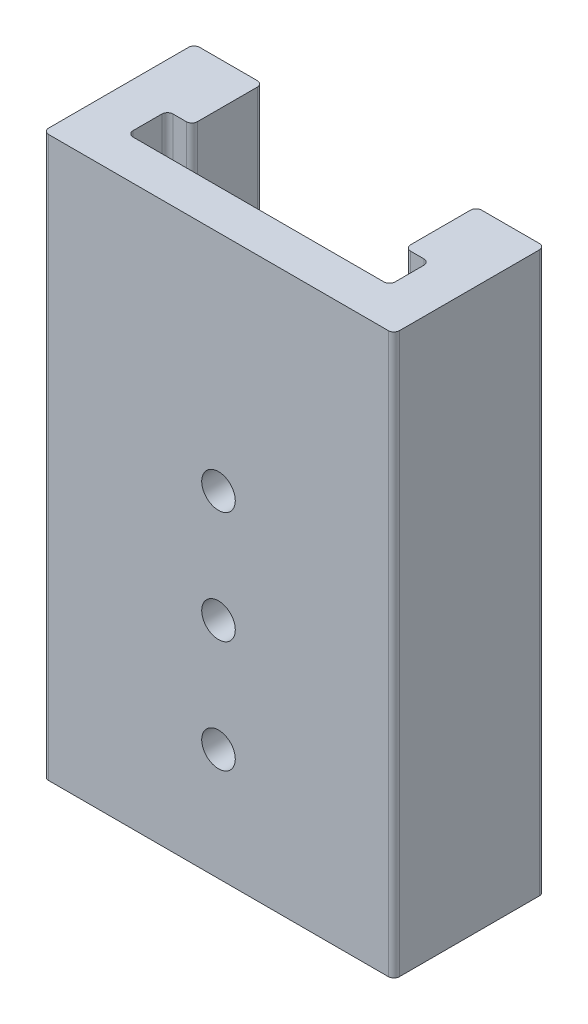
SolidWorks part; units mm, degrees
ref_plane "Front Plane" through (0, 0, 0) normal (0, 0, 1) x (1, 0, 0)
ref_plane "Top Plane" through (0, 0, 0) normal (0, 1, 0) x (1, 0, 0)
ref_plane "Right Plane" through (0, 0, 0) normal (1, 0, 0) x (0, 0, -1)
sketch "Sketch1" plane through (0, 0, 0) normal (0, 1, 0) x (1, 0, 0)
  line L0 (-15.1766, 0) -> (15.1766, 0)
  line L1 (15.6766, 0.5) -> (15.6766, 12.9937)
  line L2 (15.1766, 13.4938) -> (10.025, 13.4938)
  line L3 (9.525, 12.9937) -> (9.525, 7.6438)
  line L4 (10.025, 7.1437) -> (11.2078, 7.1437)
  line L5 (11.7078, 6.6437) -> (11.7078, 4.0719)
  line L6 (11.2078, 3.5719) -> (-11.2078, 3.5719)
  line L7 (0, 3.5719) -> (0, 0) construction
  line L8 (-11.7078, 6.6437) -> (-11.7078, 4.0719)
  line L9 (-10.025, 7.1437) -> (-11.2078, 7.1437)
  line L10 (-9.525, 12.9937) -> (-9.525, 7.6438)
  line L11 (-15.1766, 13.4937) -> (-10.025, 13.4938)
  line L12 (-15.6766, 0.5) -> (-15.6766, 12.9937)
  arc A0 (-15.6766, 0.5) -> (-15.1766, 0) centre (-15.1766, 0.5) ccw
  arc A1 (15.1766, 0) -> (15.6766, 0.5) centre (15.1766, 0.5) ccw
  arc A2 (15.6766, 12.9937) -> (15.1766, 13.4938) centre (15.1766, 12.9938) ccw
  arc A3 (10.025, 13.4938) -> (9.525, 12.9937) centre (10.025, 12.9938) ccw
  arc A4 (9.525, 7.6438) -> (10.025, 7.1437) centre (10.025, 7.6437) ccw
  arc A5 (11.2078, 7.1437) -> (11.7078, 6.6437) centre (11.2078, 6.6437) cw
  arc A6 (11.7078, 4.0719) -> (11.2078, 3.5719) centre (11.2078, 4.0719) cw
  arc A7 (-11.7078, 4.0719) -> (-11.2078, 3.5719) centre (-11.2078, 4.0719) ccw
  arc A8 (-11.7078, 6.6437) -> (-11.2078, 7.1437) centre (-11.2078, 6.6437) cw
  arc A9 (-10.025, 7.1437) -> (-9.525, 7.6438) centre (-10.025, 7.6437) ccw
  arc A10 (-9.525, 12.9937) -> (-10.025, 13.4938) centre (-10.025, 12.9938) ccw
  arc A11 (-15.1766, 13.4937) -> (-15.6766, 12.9937) centre (-15.1766, 12.9937) ccw
  point P17 (-15.6766, 0)
  point P20 (15.6766, 0)
  point P23 (15.6766, 13.4938)
  point P26 (9.525, 13.4938)
  point P29 (9.525, 7.1437)
  point P32 (11.7078, 7.1437)
  point P35 (11.7078, 3.5719)
  point P38 (-11.7078, 3.5719)
  point P41 (-11.7078, 7.1437)
  point P44 (-9.525, 7.1437)
  point P47 (-9.525, 13.4938)
  point P50 (-15.6766, 13.4937)
  dimension "D7" = 0.5
  dimension "D1" = 13.4937
  dimension "D2" = 3.5719
  dimension "D3" = 3.5719
  dimension "D4" = 19.05
  dimension "D5" = 23.4156
  dimension "D6" = 31.3531
extrude "Boss-Extrude1" add sketch "Sketch1" along normal blind 50
sketch "Sketch2" plane through (0, 0, 0) normal (0, 0, 1) x (1, 0, 0)
  circle A0 centre (0, 10) radius 1.5
  circle A1 centre (0, 20) radius 1.5
  circle A2 centre (0, 30) radius 1.5
  dimension "D1" = 3
  dimension "D3" = 10
  dimension "D4" = 10
  dimension "D2" = 3
extrude "Cut-Extrude1" cut sketch "Sketch2" against normal up to next
